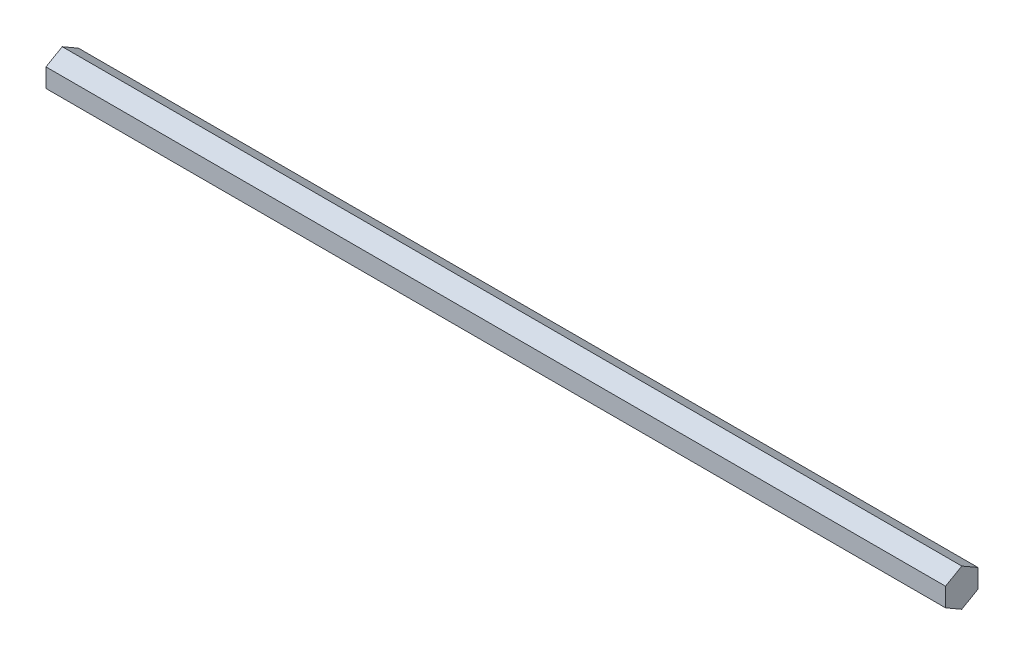
SolidWorks part; units mm, degrees
ref_plane "Front Plane" through (0, 0, 0) normal (0, 0, 1) x (1, 0, 0)
ref_plane "Top Plane" through (0, 0, 0) normal (0, 1, 0) x (1, 0, 0)
ref_plane "Right Plane" through (0, 0, 0) normal (1, 0, 0) x (0, 0, -1)
sketch "Hex Profile" plane through (0, 0, 0) normal (1, 0, 0) x (0, 0, -1)
  line L1 (4.1244, -2.3813) -> (4.1244, 2.3813)
  line L2 (4.1244, 2.3813) -> (0, 4.7625)
  line L3 (0, 4.7625) -> (-4.1244, 2.3813)
  line L4 (-4.1244, 2.3813) -> (-4.1244, -2.3813)
  line L5 (-4.1244, -2.3813) -> (0, -4.7625)
  line L6 (0, -4.7625) -> (4.1244, -2.3813)
  circle A0 centre (0, 0) radius 4.7625 construction
  dimension "D1" = 9.525
extrude "Axle" add sketch "Hex Profile" along normal blind 228.6
sketch "Motor Shaft Profile" plane through (0, 0, 0) normal (-1, 0, 0) x (0, 0, 1)
  line L0 (-1.6695, 2.4892) -> (1.6695, 2.4892)
  line L1 (0, -2.9972) -> (0, 2.4892) construction
  arc A0 (-1.6695, 2.4892) -> (1.6695, 2.4892) centre (0, 0) ccw
  arc A1 (1.6695, 2.4892) -> (-1.6695, 2.4892) centre (0, 0) ccw construction
  dimension "D1" = 5.9944
  dimension "D2" = 5.4864
extrude "Drive  Slot" cut sketch "Motor Shaft Profile" against normal blind 13.97
